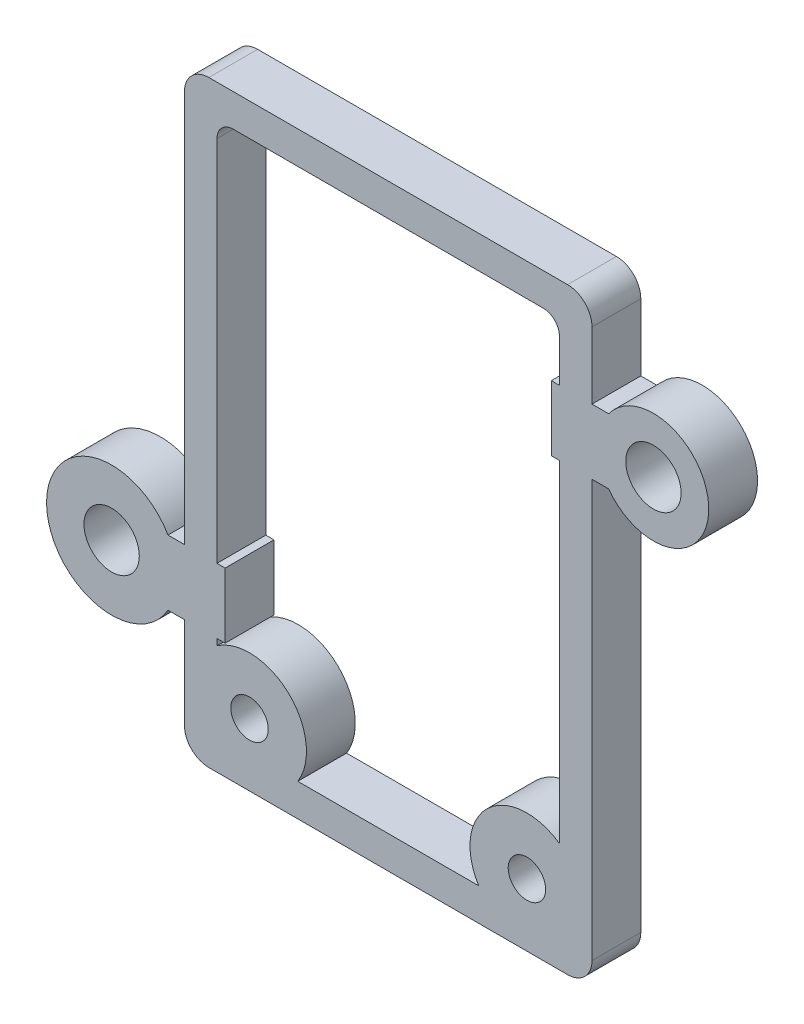
SolidWorks part; units mm, degrees
ref_plane "前视基准面" through (0, 0, 0) normal (0, 0, 1) x (1, 0, 0)
ref_plane "上视基准面" through (0, 0, 0) normal (0, 1, 0) x (1, 0, 0)
ref_plane "右视基准面" through (0, 0, 0) normal (1, 0, 0) x (0, 0, -1)
other "Configuration Table"
sketch "草图1" plane through (0, 0, 0) normal (0, 0, 1) x (1, 0, 0)
  line L0 (1, -0.5) -> (23.05, -0.5)
  line L1 (24.55, 1) -> (24.55, 34.73)
  line L2 (23.05, 36.23) -> (1, 36.23)
  line L3 (-0.5, 34.73) -> (-0.5, 1)
  line L4 (2.5, 1.5) -> (21.55, 1.5)
  line L5 (22.55, 2.5) -> (22.55, 33.23)
  line L6 (21.55, 34.23) -> (2.5, 34.23)
  line L7 (1.5, 33.23) -> (1.5, 2.5)
  arc A0 (23.05, -0.5) -> (24.55, 1) centre (23.05, 1) ccw
  arc A1 (24.55, 34.73) -> (23.05, 36.23) centre (23.05, 34.73) ccw
  arc A2 (1, 36.23) -> (-0.5, 34.73) centre (1, 34.73) ccw
  arc A3 (-0.5, 1) -> (1, -0.5) centre (1, 1) ccw
  arc A4 (21.55, 1.5) -> (22.55, 2.5) centre (21.55, 2.5) ccw
  arc A5 (22.55, 33.23) -> (21.55, 34.23) centre (21.55, 33.23) ccw
  arc A6 (2.5, 34.23) -> (1.5, 33.23) centre (2.5, 33.23) ccw
  arc A7 (1.5, 2.5) -> (2.5, 1.5) centre (2.5, 2.5) ccw
extrude "PCB_edge_support" add sketch "草图1" along normal blind 3
sketch "草图2" plane through (0, 0, 0) normal (0, 0, 1) x (1, 0, 0)
  circle A0 centre (3.5, 3.36) radius 3.5
  circle A1 centre (20.55, 3.36) radius 3.5
extrude "PCB_screw_lands" add sketch "草图2" along normal blind 3
sketch "草图3" plane through (0, 0, 0) normal (0, 0, 1) x (1, 0, 0)
  line L0 (-4.975, 6.62) -> (2, 6.62)
  line L1 (2, 6.62) -> (2, 10.62)
  line L2 (2, 10.62) -> (-4.975, 10.62)
  line L3 (-4.975, 10.62) -> (-4.975, 6.62)
  line L4 (22.05, 26.62) -> (28.025, 26.62)
  line L5 (28.025, 26.62) -> (28.025, 30.62)
  line L6 (28.025, 30.62) -> (22.05, 30.62)
  line L7 (22.05, 30.62) -> (22.05, 26.62)
extrude "Floating_mount_bridges" add sketch "草图3" along normal blind 3
sketch "草图4" plane through (0, 0, 0) normal (0, 0, 1) x (1, 0, 0)
  circle A0 centre (-4.975, 8.62) radius 4
  circle A1 centre (28.325, 28.62) radius 3.4
extrude "Floating_mount_ears" add sketch "草图4" along normal blind 3
sketch "草图5" plane through (0, 0, 0) normal (0, 0, 1) x (1, 0, 0)
  circle A0 centre (3.5, 3.36) radius 1.15
  circle A1 centre (20.55, 3.36) radius 1.15
extrude "PCB_M2_clearance" cut sketch "草图5" along normal blind 4
sketch "草图6" plane through (0, 0, 0) normal (0, 0, 1) x (1, 0, 0)
  circle A0 centre (-4.975, 8.62) radius 1.7
  circle A1 centre (28.325, 28.62) radius 1.7
extrude "M2_adjustment_0p7" cut sketch "草图6" along normal blind 4
